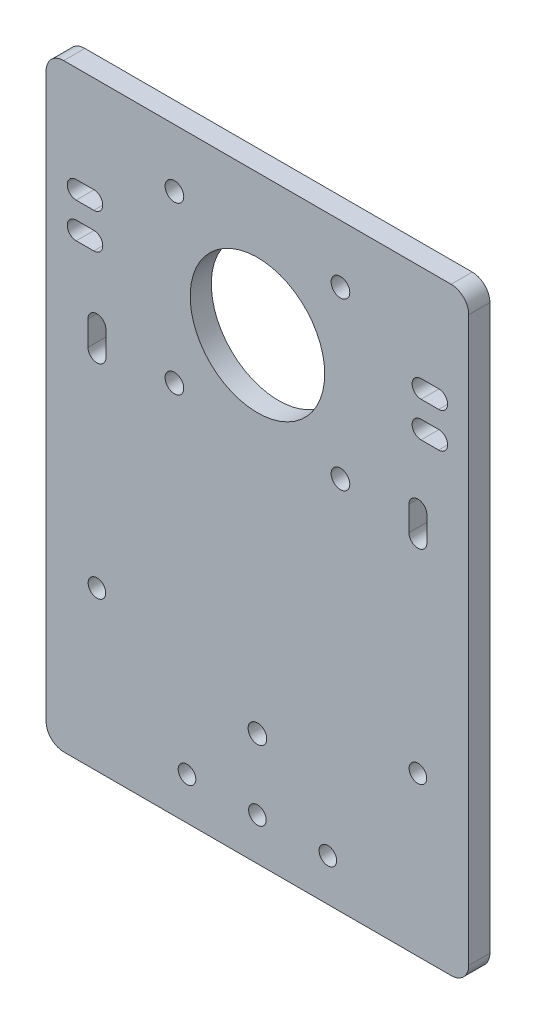
SolidWorks part; units mm, degrees
ref_plane "Front Plane" through (0, 0, 0) normal (0, 0, 1) x (1, 0, 0)
ref_plane "Top Plane" through (0, 0, 0) normal (0, 1, 0) x (1, 0, 0)
ref_plane "Right Plane" through (0, 0, 0) normal (1, 0, 0) x (0, 0, -1)
sketch "Sketch1" plane through (0, 0, 0) normal (0, 0, 1) x (1, 0, 0)
  line L1 (-55, -85) -> (55, -85)
  line L2 (-60, -80) -> (-60, 80)
  line L3 (-55, 85) -> (55, 85)
  line L4 (60, -80) -> (60, 80)
  line L5 (-60, -85) -> (60, 85) construction
  line L6 (-60, 85) -> (60, -85) construction
  arc A0 (-55, -85) -> (-60, -80) centre (-55, -80) cw
  arc A1 (55, -85) -> (60, -80) centre (55, -80) ccw
  arc A2 (55, 85) -> (60, 80) centre (55, 80) cw
  arc A3 (-60, 80) -> (-55, 85) centre (-55, 80) cw
  point P0 (0, 0)
  dimension "D3" = 5
  dimension "D1" = 170
  dimension "D2" = 120
extrude "Boss-Extrude1" add sketch "Sketch1" along normal blind 6
sketch "Sketch3" plane through (0, 0, 6) normal (0, 0, 1) x (1, 0, 0)
  line L0 (55, 85) -> (-55, 85) construction
  circle A0 centre (0, 45) radius 19.1
  point P6 (0, 85)
  dimension "D1" = 40
  dimension "D2" = 38.2
extrude "Cut-Extrude1" cut sketch "Sketch3" against normal blind 6
hole_wizard "M5 Clearance Hole1" positions "Sketch8" profile "Sketch9" hole size "M5" standard "ANSI Metric" end condition through all
sketch "Sketch8" plane through (0, 0, 6) normal (0, 0, 1) x (1, 0, 0)
  circle A0 centre (0, 45) radius 19.1 construction
  point P0 (-23.57, 68.57)
  point P2 (23.57, 68.57)
  point P4 (23.57, 21.43)
  point P6 (-23.57, 21.43)
  dimension "D2" = 23.57
  dimension "D3" = 23.57
  dimension "D4" = 23.57
  dimension "D5" = 23.57
  dimension "D1" = 23.57
sketch "Sketch9" plane through (-23.57, 68.57, 6) normal (1, 0, 0) x (0, -1, 0)
  line L0 (0, 0) -> (0, 6)
  line L1 (0, 6) -> (2.65, 6)
  line L2 (2.65, 6) -> (2.65, 0)
  line L5 (2.65, 0) -> (0, 0)
  line L11 (0, -6.35) -> (0, 107.95) construction
  dimension "Thru Hole Dia." = 5.3
  dimension "Thru Hole Depth" = 6
sketch "Sketch11" plane through (0, 0, 6) normal (0, 0, 1) x (1, 0, 0)
  line L0 (-45.57, 24.93) -> (-45.57, 17.93) construction
  line L1 (-43.03, 24.93) -> (-43.03, 17.93)
  line L2 (-48.11, 24.93) -> (-48.11, 17.93)
  line L5 (0, 63.1141) -> (0, -86.0691) construction
  line L8 (45.57, 24.93) -> (45.57, 17.93) construction
  line L9 (43.03, 24.93) -> (43.03, 17.93)
  line L10 (48.11, 24.93) -> (48.11, 17.93)
  arc A0 (-43.03, 24.93) -> (-48.11, 24.93) centre (-45.57, 24.93) ccw
  arc A1 (-48.11, 17.93) -> (-43.03, 17.93) centre (-45.57, 17.93) ccw
  circle A3 centre (-23.57, 21.43) radius 2.65 construction
  arc A4 (43.03, 24.93) -> (48.11, 24.93) centre (45.57, 24.93) cw
  arc A5 (48.11, 17.93) -> (43.03, 17.93) centre (45.57, 17.93) cw
  point P2 (-45.57, 21.43)
  point P15 (45.57, 21.43)
  dimension "D2" = 2.54
  dimension "D1" = 7
  dimension "D3" = 22
extrude "Cut-Extrude2" cut sketch "Sketch11" against normal blind 6
sketch "Sketch15" plane through (0, 0, 6) normal (0, 0, 1) x (1, 0, 0)
  line L0 (-51.46, 45) -> (-46.46, 45) construction
  line L1 (-51.46, 47.54) -> (-46.46, 47.54)
  line L2 (-51.46, 42.46) -> (-46.46, 42.46)
  line L3 (-51.46, 55) -> (-46.46, 55) construction
  line L4 (-51.46, 57.54) -> (-46.46, 57.54)
  line L5 (-51.46, 52.46) -> (-46.46, 52.46)
  line L6 (-60, 80) -> (-60, -80) construction
  line L8 (55, 85) -> (-55, 85) construction
  line L9 (0, 75.2932) -> (0, -13.323) construction
  line L10 (0, 63.1141) -> (0, -86.0691) construction
  line L11 (51.46, 45) -> (46.46, 45) construction
  line L12 (51.46, 47.54) -> (46.46, 47.54)
  line L13 (51.46, 42.46) -> (46.46, 42.46)
  line L14 (51.46, 55) -> (46.46, 55) construction
  line L15 (51.46, 57.54) -> (46.46, 57.54)
  line L16 (51.46, 52.46) -> (46.46, 52.46)
  arc A0 (-51.46, 47.54) -> (-51.46, 42.46) centre (-51.46, 45) ccw
  arc A1 (-46.46, 42.46) -> (-46.46, 47.54) centre (-46.46, 45) ccw
  arc A2 (-51.46, 57.54) -> (-51.46, 52.46) centre (-51.46, 55) ccw
  arc A3 (-46.46, 52.46) -> (-46.46, 57.54) centre (-46.46, 55) ccw
  arc A5 (51.46, 47.54) -> (51.46, 42.46) centre (51.46, 45) cw
  arc A6 (46.46, 42.46) -> (46.46, 47.54) centre (46.46, 45) cw
  arc A7 (51.46, 57.54) -> (51.46, 52.46) centre (51.46, 55) cw
  arc A8 (46.46, 52.46) -> (46.46, 57.54) centre (46.46, 55) cw
  point P2 (-48.96, 45)
  point P7 (-48.96, 55)
  point P15 (-54, 45)
  point P32 (48.96, 45)
  point P39 (48.96, 55)
  dimension "D1" = 30
  dimension "D2" = 2.54
  dimension "D4" = 5
  dimension "D5" = 6
  dimension "D6" = 10
extrude "Cut-Extrude4" cut sketch "Sketch15" against normal blind 6
hole_wizard "Ø5.0 (5) Diameter Hole4" positions "Sketch17" profile "Sketch18" hole size "Ø5.0" standard "ANSI Metric" end condition through all
sketch "Sketch17" plane through (0, 0, 6) normal (0, 0, 1) x (1, 0, 0)
  line L1 (-55, -85) -> (55, -85) construction
  line L2 (60, -80) -> (60, 80) construction
  line L3 (-60, 80) -> (-60, -80) construction
  point P0 (-45.57, -39.97)
  point P2 (45.57, -39.97)
  point P4 (20, -73)
  point P6 (0, -73)
  point P8 (-20, -73)
  dimension "D3" = 40
  dimension "D1" = 61.4
  dimension "D2" = 12
  dimension "D4" = 40
sketch "Sketch18" plane through (-45.57, -39.97, 6) normal (1, 0, 0) x (0, -1, 0)
  line L0 (0, 0) -> (0, 6)
  line L1 (0, 6) -> (2.5, 6)
  line L2 (2.5, 6) -> (2.5, 0)
  line L5 (2.5, 0) -> (0, 0)
  line L11 (0, -6.35) -> (0, 107.95) construction
  dimension "Thru Hole Dia." = 5
  dimension "Thru Hole Depth" = 6
hole_wizard "M5 Clearance Hole2" positions "Sketch19" profile "Sketch20" hole size "M5" standard "ANSI Metric"
sketch "Sketch19" plane through (0, 0, 0) normal (0, 0, -1) x (-1, 0, 0)
  circle A0 centre (0, -73) radius 2.5 construction
  point P0 (0, -53)
  point P5 (0, 0)
  dimension "D1" = 20
sketch "Sketch20" plane through (0, -53, 0) normal (1, 0, 0) x (0, 1, 0)
  line L0 (0, 0) -> (0, 11.5923)
  line L1 (0, 11.5923) -> (2.65, 10)
  line L2 (2.65, 10) -> (2.65, 0)
  line L5 (2.65, 0) -> (0, 0)
  line L10 (0, 11.5923) -> (-2.65, 10) construction
  line L11 (0, -6.35) -> (0, 107.95) construction
  dimension "Hole Dia." = 5.3
  dimension "Hole Depth" = 10
  dimension "Drill Angle" = 118
